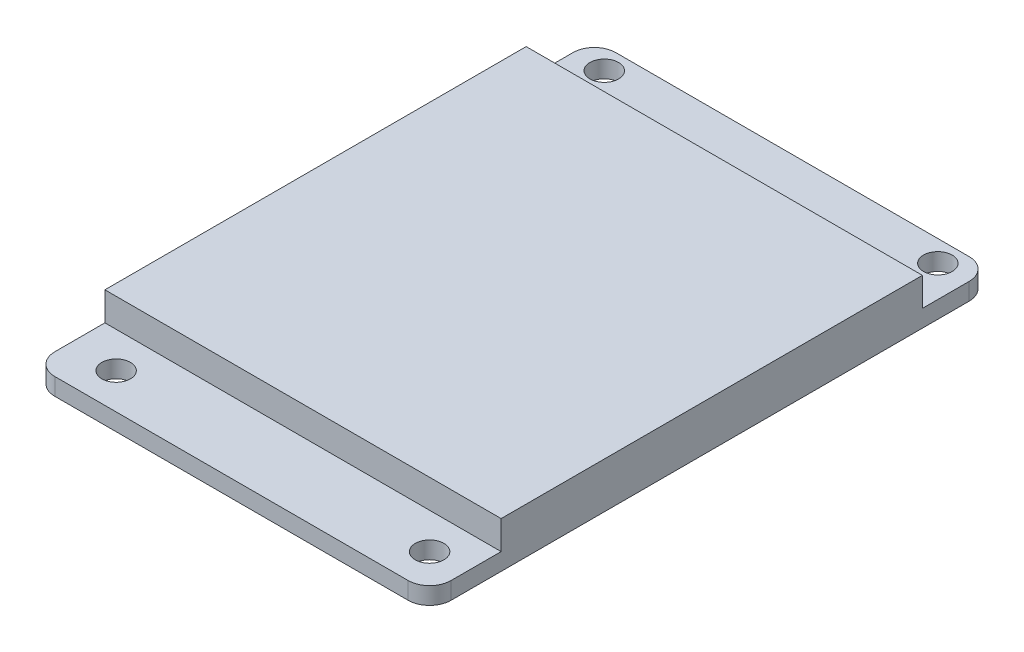
SolidWorks part; units mm, degrees
ref_plane "Front Plane" through (0, 0, 0) normal (0, 0, 1) x (1, 0, 0)
ref_plane "Top Plane" through (0, 0, 0) normal (0, 1, 0) x (1, 0, 0)
ref_plane "Right Plane" through (0, 0, 0) normal (1, 0, 0) x (0, 0, -1)
sketch "Sketch1" plane through (0, 0, 0) normal (0, 1, 0) x (1, 0, 0)
  line L1 (1.5, 0) -> (26.2, 0)
  line L2 (0, 1.5) -> (0, 37.72)
  line L3 (1.5, 39.22) -> (26.2, 39.22)
  line L4 (27.7, 1.5) -> (27.7, 37.72)
  line L7 (0, 34.22) -> (0, 5)
  line L9 (27.7, 34.22) -> (27.7, 5)
  circle A0 centre (2.19, 37.72) radius 1
  circle A1 centre (25.51, 37.72) radius 1
  circle A2 centre (3.2861, 2.5) radius 1
  circle A3 centre (25.2, 2.5) radius 1
  arc A4 (1.5, 0) -> (0, 1.5) centre (1.5, 1.5) cw
  arc A5 (26.2, 0) -> (27.7, 1.5) centre (26.2, 1.5) ccw
  arc A6 (26.2, 39.22) -> (27.7, 37.72) centre (26.2, 37.72) cw
  arc A7 (0, 37.72) -> (1.5, 39.22) centre (1.5, 37.72) cw
  point P13 (3.2861, 2.6599)
  point P14 (2.8203, 37.72)
  point P18 (0, 0)
  point P23 (27.7, 39.22)
  point P26 (0, 39.22)
  dimension "D3" = 2
  dimension "D8" = 1.5
  dimension "D1" = 39.22
  dimension "D2" = 27.7
  dimension "D4" = 1.5
  dimension "D5" = 2.19
  dimension "D6" = 2.19
  dimension "D7" = 2.5
  dimension "D11" = 2.5
extrude "Boss-Extrude1" add sketch "Sketch1" along normal blind 1.2 contours A7 L2 A4 L1 A5 L4 A6 L3 A3 A2 A1 A0
sketch "Sketch2" plane through (0, 1.2, 0) normal (0, 1, 0) x (1, 0, 0)
  line L0 (0, 1.5) -> (0, 37.72) construction
  line L1 (0, 34.4507) -> (27.7, 34.4507)
  line L2 (0, 34.4507) -> (0, 5)
  line L3 (0, 5) -> (27.7, 5)
  line L4 (27.7, 34.4507) -> (27.7, 5)
  line L5 (27.7, 1.5) -> (27.7, 37.72) construction
  line L6 (1.5, 0) -> (26.2, 0) construction
  dimension "D1" = 5
extrude "Boss-Extrude2" add sketch "Sketch2" along normal blind 2
